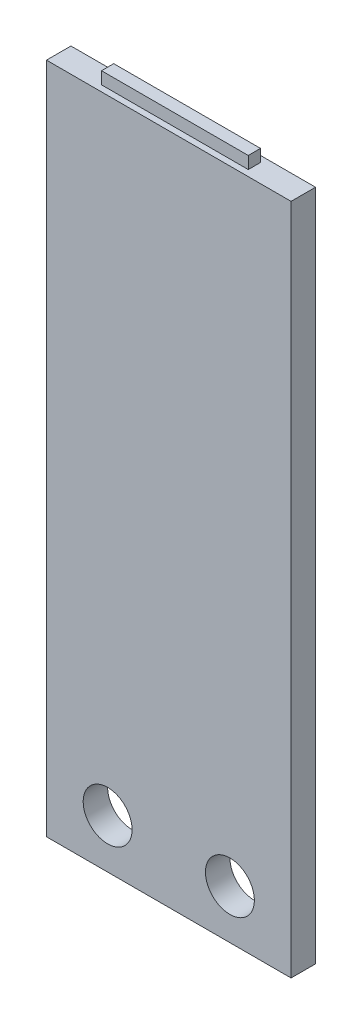
SolidWorks part; units mm, degrees
ref_plane "Front Plane" through (0, 0, 0) normal (0, 0, 1) x (1, 0, 0)
ref_plane "Top Plane" through (0, 0, 0) normal (0, 1, 0) x (1, 0, 0)
ref_plane "Right Plane" through (0, 0, 0) normal (1, 0, 0) x (0, 0, -1)
sketch "Sketch1" plane through (0, 0, 0) normal (0, 0, 1) x (1, 0, 0)
  line L1 (50, -137.5) -> (-50, -137.5)
  line L2 (50, -137.5) -> (50, 137.5)
  line L3 (50, 137.5) -> (-50, 137.5)
  line L4 (-50, -137.5) -> (-50, 137.5)
  line L5 (50, -137.5) -> (-50, 137.5) construction
  line L6 (50, 137.5) -> (-50, -137.5) construction
  point P0 (0, 0)
extrude "Boss-Extrude1" add sketch "Sketch1" along normal blind 10
sketch "Sketch2" plane through (0, 137.5, 0) normal (0, 1, 0) x (1, 0, 0)
  line L0 (0, 0) -> (0, -10) construction
  line L1 (50, -10) -> (-50, -10) construction
  line L3 (30, -7.5) -> (-30, -7.5)
  line L4 (30, -7.5) -> (30, -2.5)
  line L5 (30, -2.5) -> (-30, -2.5)
  line L6 (-30, -7.5) -> (-30, -2.5)
  line L7 (30, -7.5) -> (-30, -2.5) construction
  line L8 (30, -2.5) -> (-30, -7.5) construction
  point P5 (0, -5)
extrude "Boss-Extrude2" add sketch "Sketch2" along normal blind 5
sketch "Sketch3" plane through (0, 0, 10) normal (0, 0, 1) x (1, 0, 0)
  line L0 (0, -137.5) -> (0, -117.5) construction
  line L1 (-50, -137.5) -> (50, -137.5) construction
  line L2 (0, -117.5) -> (50, -117.5) construction
  line L3 (50, -137.5) -> (50, 137.5) construction
  circle A0 centre (25, -117.5) radius 10
  circle A1 centre (-25, -117.5) radius 10
extrude "Cut-Extrude1" cut sketch "Sketch3" against normal through all
